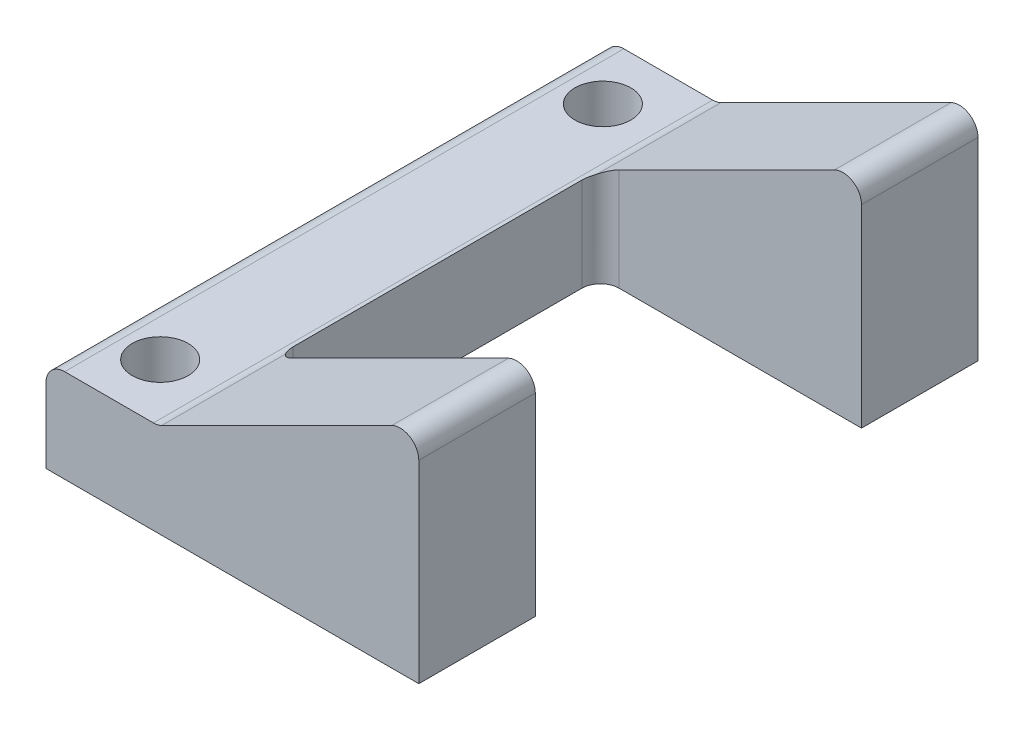
SolidWorks part; units mm, degrees
ref_plane "前视基准面" through (0, 0, 0) normal (0, 0, 1) x (1, 0, 0)
ref_plane "上视基准面" through (0, 0, 0) normal (0, 1, 0) x (1, 0, 0)
ref_plane "右视基准面" through (0, 0, 0) normal (1, 0, 0) x (0, 0, -1)
sketch "Sketch1" plane through (0, 0, 0) normal (0, 0, 1) x (1, 0, 0)
  line L0 (0, 0) -> (0, 4)
  line L2 (20, 10.382) -> (20, 0)
  line L3 (20, 0) -> (0, 0)
  line L4 (1, 5) -> (5.7639, 5)
  line L5 (6.2111, 5.1056) -> (18.5528, 11.2764)
  arc A1 (0, 4) -> (1, 5) centre (1, 4) cw
  arc A2 (5.7639, 5) -> (6.2111, 5.1056) centre (5.7639, 6) ccw
  arc A3 (18.5528, 11.2764) -> (20, 10.382) centre (19, 10.382) cw
  point P7 (20, 0)
  point P11 (0, 5)
  point P14 (6, 5)
  point P17 (20, 12)
  dimension "D1" = 5
  dimension "D2" = 6
  dimension "D3" = 12
  dimension "D4" = 20
extrude "Boss-Extrude1" add sketch "Sketch1" along normal mid plane 30
sketch "Sketch2" plane through (0, 0, 0) normal (0, -1, 0) x (1, 0, 0)
  line L1 (0, 15) -> (0, -15) construction
  line L3 (27.5831, 0) -> (-6.4229, 0) construction
  line L6 (20, -8.75) -> (20, 8.75)
  line L7 (20, 15) -> (20, -15) construction
  line L8 (20, 8.75) -> (7, 8.75)
  line L9 (6, 7.75) -> (6, -7.75)
  line L10 (20, -8.75) -> (7, -8.75)
  arc A0 (7, -8.75) -> (6, -7.75) centre (7, -7.75) cw
  arc A1 (7, 8.75) -> (6, 7.75) centre (7, 7.75) ccw
  circle A2 centre (3, 11.875) radius 1.5
  circle A3 centre (3, -11.875) radius 1.5
  point P10 (0, 0)
  point P11 (14.4787, 0)
  point P14 (6, 0)
  point P15 (20, 0)
  point P17 (6, -8.75)
  point P20 (6, 8.75)
  dimension "D3" = 1
  dimension "D4" = 3
  dimension "D1" = 17.5
  dimension "D2" = 6
  dimension "D5" = 3
  dimension "D6" = 23.75
extrude "Cut-Extrude1" cut sketch "Sketch2" against normal blind 30
